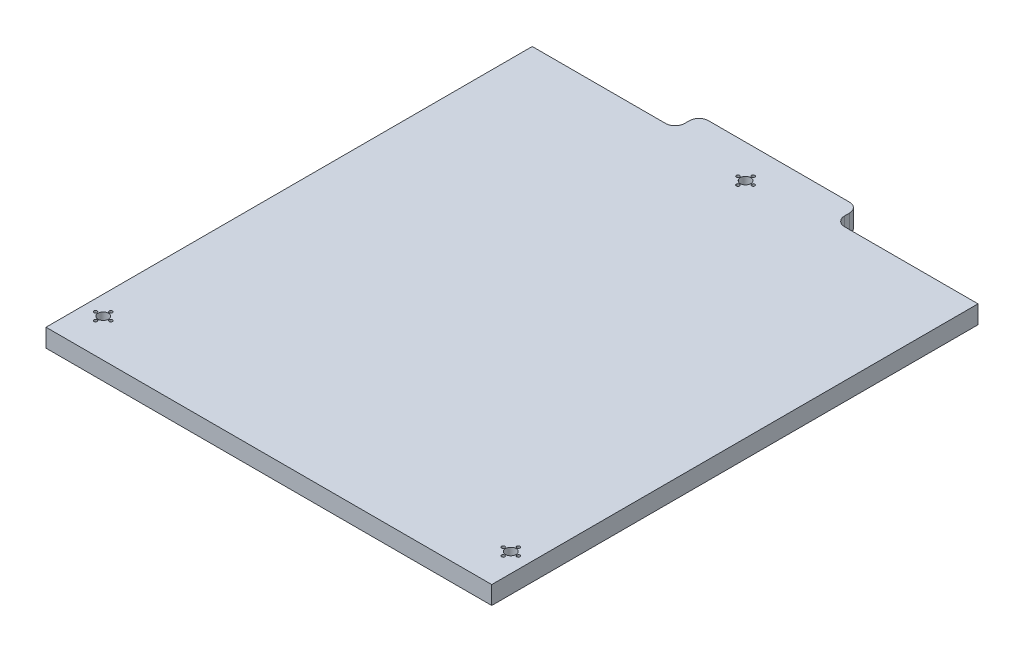
SolidWorks part; units mm, degrees
ref_plane "Front Plane" through (0, 0, 0) normal (0, 0, 1) x (1, 0, 0)
ref_plane "Top Plane" through (0, 0, 0) normal (0, 1, 0) x (1, 0, 0)
ref_plane "Right Plane" through (0, 0, 0) normal (1, 0, 0) x (0, 0, -1)
sketch "Sketch2" plane through (0, 0, 0) normal (0, 1, 0) x (1, 0, 0)
  line L0 (233.75, 0) -> (233.75, 535) construction
  line L1 (0, 0) -> (467.5, 0)
  line L2 (0, 0) -> (0, 510)
  line L3 (317.6528, 535) -> (149.8472, 535)
  line L4 (467.5, 0) -> (467.5, 510)
  line L5 (149.8472, 535) -> (149.8472, 510)
  line L6 (149.8472, 510) -> (0, 510)
  line L7 (317.6528, 510) -> (467.5, 510)
  line L8 (317.6528, 535) -> (317.6528, 510)
  circle A0 centre (233.75, 500) radius 5.5
  circle A1 centre (20, 40) radius 5.5
  circle A2 centre (447.5, 40) radius 5.5
  dimension "D5" = 11
  dimension "D1" = 510
  dimension "D2" = 467.5
  dimension "D6" = 460
  dimension "D7" = 20
  dimension "D8" = 40
extrude "Boss-Extrude1" add sketch "Sketch2" along normal blind 19.05
hole_wizard "M3 Clearance Hole1" positions "3DSketch1" profile "Sketch3" hole size "M3" standard "ANSI Metric" end condition through all
sketch3d "3DSketch1"
  line L0 (233.75, 19.05, -500) -> (225.75, 19.05, -500) construction
  line L1 (233.75, 19.05, -500) -> (233.75, 0, -500) construction
  point P0 (225.75, 19.05, -500)
  dimension "D1" = 8
sketch "Sketch3" plane through (225.75, 19.05, -500) normal (1, 0, 0) x (0, 0, 1)
  line L0 (0, 0) -> (0, 19.05)
  line L1 (0, 19.05) -> (1.7, 19.05)
  line L2 (1.7, 19.05) -> (1.7, 0)
  line L5 (1.7, 0) -> (0, 0)
  line L11 (0, -6.35) -> (0, 107.95) construction
  dimension "Thru Hole Dia." = 3.4
  dimension "Thru Hole Depth" = 19.05
pattern_circular "CirPattern1" count 4 every 90 about axis through (233.75, 0, -500) along (0, 1, 0) of "M3 Clearance Hole1"
fillet "Fillet1" radius 10 4 edges at (317.6528, 9.525, -510) (317.6528, 9.525, -535) (149.8472, 9.525, -535) (149.8472, 9.525, -510)
hole_wizard "M3 Clearance Hole2" positions "3DSketch2" profile "Sketch4" hole size "M3" standard "ANSI Metric" end condition through all
sketch3d "3DSketch2"
  line L2 (20, 19.05, -48) -> (20, 19.05, -40) construction
  line L3 (20, 19.05, -40) -> (20, 0, -40) construction
  circle A0 centre (20, 19.05, -40) radius 5.5 construction
  point P0 (20, 19.05, -48)
  point P5 (20, 24.55, -40)
  dimension "D1" = 8
sketch "Sketch4" plane through (20, 19.05, -48) normal (1, 0, 0) x (0, 0, 1)
  line L0 (0, 0) -> (0, 19.05)
  line L1 (0, 19.05) -> (1.7, 19.05)
  line L2 (1.7, 19.05) -> (1.7, 0)
  line L5 (1.7, 0) -> (0, 0)
  line L11 (0, -6.35) -> (0, 107.95) construction
  dimension "Thru Hole Dia." = 3.4
  dimension "Thru Hole Depth" = 19.05
pattern_circular "CirPattern2" count 4 every 90 about axis through (20, 0, -40) along (0, 1, 0) of "M3 Clearance Hole2"
hole_wizard "M3 Clearance Hole3" positions "3DSketch3" profile "Sketch6" hole size "M3" standard "ANSI Metric" end condition through all
sketch3d "3DSketch3"
  line L2 (447.5, 19.05, -48) -> (447.5, 19.05, -40) construction
  line L3 (447.5, 19.05, -40) -> (447.5, 0, -40) construction
  point P0 (447.5, 19.05, -48)
  dimension "D1" = 8
sketch "Sketch6" plane through (447.5, 19.05, -48) normal (1, 0, 0) x (0, 0, 1)
  line L0 (0, 0) -> (0, 19.05)
  line L1 (0, 19.05) -> (1.7, 19.05)
  line L2 (1.7, 19.05) -> (1.7, 0)
  line L5 (1.7, 0) -> (0, 0)
  line L11 (0, -6.35) -> (0, 107.95) construction
  dimension "Thru Hole Dia." = 3.4
  dimension "Thru Hole Depth" = 19.05
pattern_circular "CirPattern3" count 4 every 90 about axis through (447.5, 0, -40) along (0, 1, 0) of "M3 Clearance Hole3"
